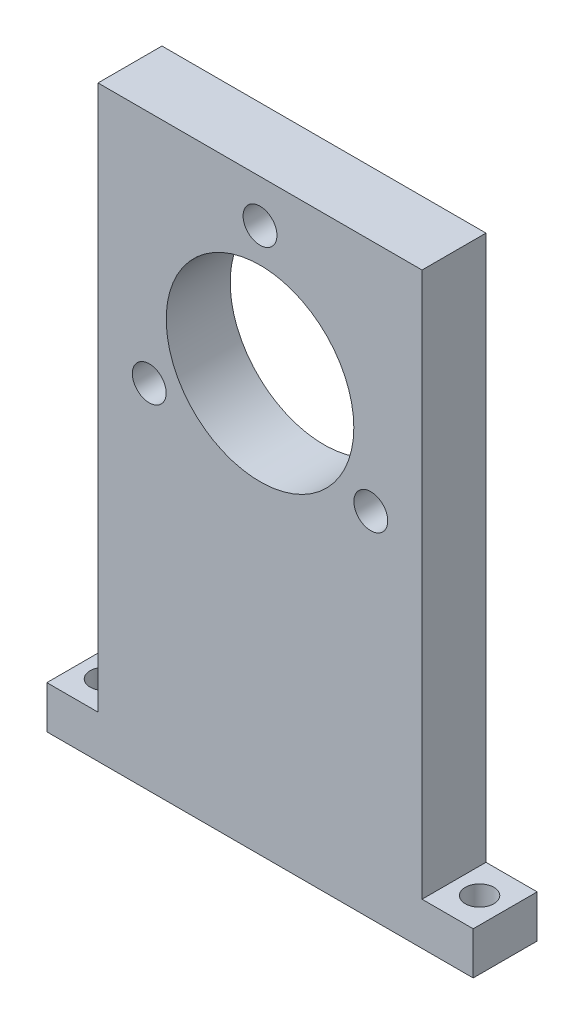
SolidWorks part; units mm, degrees
material "6061-T6 (SS)"
ref_plane "Frontal Plane" through (0, 0, 0) normal (0, 0, 1) x (1, 0, 0)
ref_plane "Horizontal Plane" through (0, 0, 0) normal (0, 1, 0) x (1, 0, 0)
ref_plane "Profile Plane" through (0, 0, 0) normal (1, 0, 0) x (0, 0, -1)
sketch "Sketch2" plane through (0, 0, 0) normal (0, 0, 1) x (1, 0, 0)
  line L0 (-25, 0) -> (25, 0)
  line L1 (25, 0) -> (25, 5)
  line L2 (25, 5) -> (19, 5)
  line L3 (19, 5) -> (19, 68.9056)
  line L4 (19, 68.9056) -> (-19, 68.9056)
  line L5 (-19, 68.9056) -> (-19, 5)
  line L6 (-19, 5) -> (-25, 5)
  line L7 (-25, 5) -> (-25, 0)
  circle A0 centre (0, 48.9056) radius 11
  point P4 (0, 0)
  point P11 (0, 68.9056)
  dimension "D2" = 22
  dimension "D1" = 38
  dimension "D3" = 5
  dimension "D5" = 48.9056
  dimension "D4" = 6
  dimension "D6" = 20
extrude "Boss-Extrude1" add sketch "Sketch2" against normal blind 7.5
ref_plane "Plane1" through (0, 0, -7.5) normal (0, 0, -1) x (-1, 0, 0)
sketch "Sketch5" plane through (0, 0, 0) normal (0, 0, 1) x (1, 0, 0)
  line L0 (0, 63.9056) -> (0, 48.9056) construction
  circle A0 centre (0, 48.9056) radius 15 construction
  circle A2 centre (0, 63.9056) radius 1.9844
  circle A5 centre (0, 48.9056) radius 11 construction
  dimension "D1" = 30
  dimension "D4" = 3.9688
extrude "Cut-Extrude3" cut sketch "Sketch5" against normal through all
pattern_circular "CirPattern1" count 3 over 360 about axis through (0, 48.9056, 0) along (0, 0, 1) of "Cut-Extrude3"
sketch "Sketch6" plane through (0, 5, 0) normal (0, 1, 0) x (1, 0, 0)
  line L0 (-25, 7.5) -> (-25, 0) construction
  line L2 (25, 7.5) -> (25, 0) construction
  circle A0 centre (22, 3.75) radius 1.675
  circle A1 centre (-22, 3.75) radius 1.675
  point P6 (-25, 3.75)
  dimension "D1" = 3.35
  dimension "D2" = 3
  dimension "D3" = 3
extrude "Cut-Extrude4" cut sketch "Sketch6" against normal through all
sketch "Sketch7" [suppressed] plane through (0, 0, 0) normal (0, 0, 1) x (1, 0, 0)
  line L1 (-54.6719, 26.3959) -> (-29.2719, 26.3959) construction
  line L2 (-54.6719, 26.3959) -> (-54.6719, 0.9959) construction
  line L3 (-54.6719, 0.9959) -> (-29.2719, 0.9959) construction
  line L4 (-29.2719, 26.3959) -> (-29.2719, 0.9959) construction
  line L5 (-54.6719, 26.3959) -> (-29.2719, 0.9959) construction
  line L6 (-54.6719, 0.9959) -> (-29.2719, 26.3959) construction
  point P0 (-41.9719, 13.6959)
  dimension "D1" = 25.4
equation "\"BaseL\"= 6ft"
equation "\"BaseW\"= 5.5in"
equation "\"BaseThickness\"= 1in"
equation "\"RailGap\"= 4cm"
equation "\"SlidePlateL\"= 8cm"
equation "\"SlidePlateW\"= 11cm"
equation "\"SlidePlateThickness\"= 5mm"
equation "\"SlidePlateClearance\"= 1cm"
equation "\"BoxThickness\"= .5cm"
equation "\"BoxX\"= \"RailGap\" + 30mm"
equation "\"BoxH\"= 2cm + \"SlidePlateClearance\" + \"SlidePlateThickness\" + 3cm"
equation "\"PulleyRadius\"= 15.1mm"
equation "\"PulleyH\"= 30mm + 21.4056mm - 2.5mm"
equation "\"PulleyShaftDiameter\"= .3125in"
equation "\"PulleyShaftL\"= 4in"
equation "\"PulleyShaft2L\"= 3in"
equation "\"MotorL\"= 4.43in"
equation "\"MotorRadius\"= 1.291in"
equation "\"MotorShaftRadius\"= .15625in"
equation "\"MotorShaftL\"= 1.75in"
equation "\"HeadstoneThickness\"= 7.5mm"
equation "\"BeltL\"= 1500mm + \"80\""
equation "\"BeltThickness\"= 2.5mm"
equation "\"BeltW\"= .375in"
equation "\"BeltLockH\"= \"PulleyH\" + 19.4056mm - (\"SlidePlateThickness\" + \"SlidePlateClearance\" + 15mm + 5mm)"
equation "\"EncoderL\"= 33mm"
equation "\"EncoderRadius\"= 19mm"
equation "\"EncoderShaftRadius\"= 3mm"
equation "\"EncoderShaftL\"= 15mm"
equation "\"PendulumShaftL\"= \"100mm\" "
equation "\"PendulumShaftRadius\"= 3mm"
equation "\"RodL\"= 39in"
equation "\"RodRadius\"= 3mm"
equation "\"D1@Sketch2\"=\"EncoderRadius\"*2"
equation "\"PillowBlockCenterH\"= \"EncoderRadius\" + 2mm"
equation "\"D5@Sketch2\"=\"PulleyH\""
